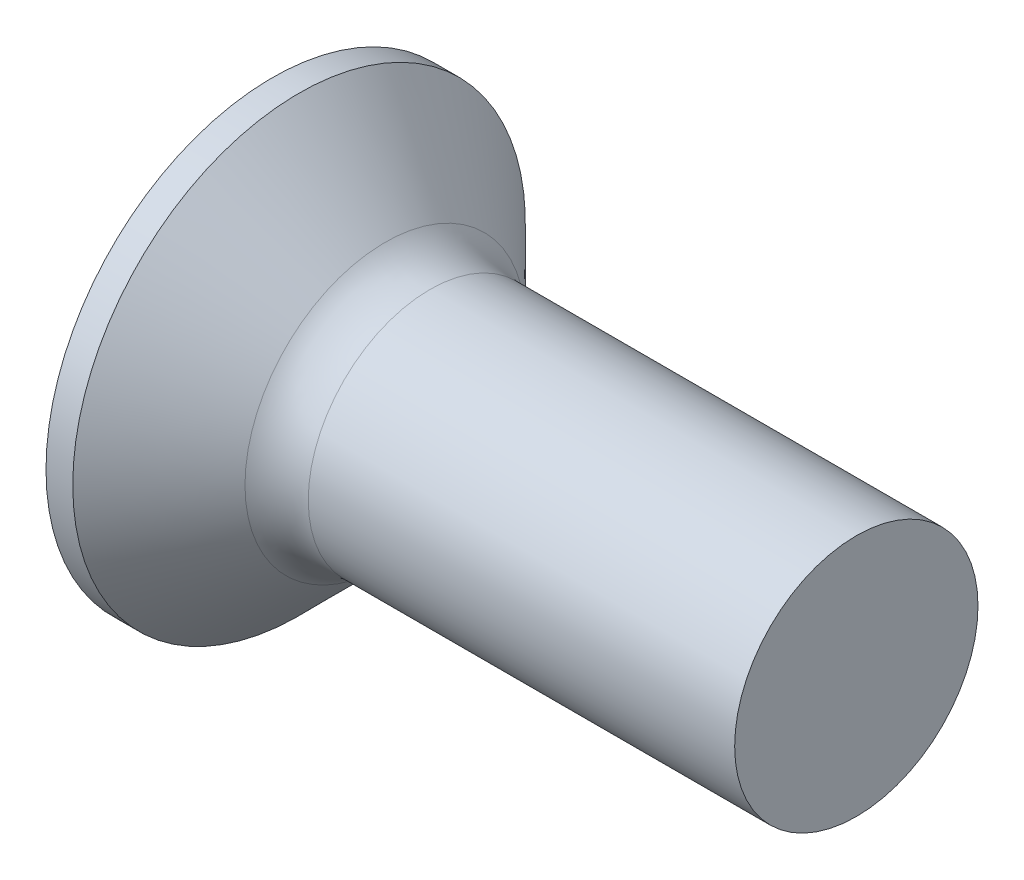
SolidWorks part; units mm, degrees
ref_plane "Plane1" through (0, 0, 0) normal (0, 0, 1) x (1, 0, 0)
ref_plane "Plane2" through (0, 0, 0) normal (0, 1, 0) x (1, 0, 0)
ref_plane "Plane3" through (0, 0, 0) normal (1, 0, 0) x (0, 0, -1)
sketch "BodySke" plane through (0, 0, 0) normal (0, 0, 1) x (1, 0, 0)
  line L0 (0, 0) -> (0, 4.65)
  line L1 (0, 4.65) -> (0.55, 4.65)
  line L2 (2.7, 2.5) -> (12, 2.5)
  line L3 (12, 2.5) -> (12, 0)
  line L4 (12, 0) -> (0, 0)
  line L5 (-6.35, 0) -> (82.55, 0) construction
  line L6 (2.7, -2.5) -> (12, -2.5) construction
  line L7 (0.55, -4.65) -> (2.7, -2.5) construction
  line L8 (0.55, 4.65) -> (2.7, 2.5)
  line L9 (0, -4.65) -> (0.55, -4.65) construction
  line L10 (3.5, 4.0875) -> (3.5, -5.4375) construction
  line L11 (0, 6.35) -> (0, -3.175) construction
  dimension "Diameter" = 5
  dimension "Length" = 12
  dimension "Head_ht" = 2.7
  dimension "Head_dia" = 9.3
  dimension "Head_ang" = 90
  dimension "D6" = 0.55
  dimension "Advance" = 0.8
  dimension "Thread_nom" = 12
revolve "Base-Revolve" add sketch "BodySke"
cosmetic thread "ThreadCosmetic" [suppressed]
fillet "Fillet1" radius 1.3 1 edges at (2.7, 0, 2.5)
sketch "Sketch3" plane through (0, 0, 0) normal (-1, 0, 0) x (0, 0, 1)
  line L0 (-0.515, 2.45) -> (0.515, 2.45)
  line L1 (0.515, 2.45) -> (0.515, -2.45)
  line L2 (0.515, -2.45) -> (-0.515, -2.45)
  line L3 (-0.515, -2.45) -> (-0.515, 2.45)
  dimension "D1" = 2.45
  dimension "Cross_dia" = 4.9
  dimension "D2" = 0.515
  dimension "Cross_width" = 1.03
ref_plane "Plane4" through (3.05, 0, 0) normal (-1, 0, 0) x (0, 0, 1)
sketch "Sketch4" plane through (3.05, 0, 0) normal (-1, 0, 0) x (0, 0, 1)
  line L0 (-0.515, 0.9293) -> (0.515, 0.9293)
  line L3 (0.515, 0.9293) -> (0.515, -0.9293)
  line L4 (0.515, -0.9293) -> (-0.515, -0.9293)
  line L5 (-0.515, -0.9293) -> (-0.515, 0.9293)
  dimension "D1" = 1.03
  dimension "D2" = 1.8587
  dimension "D3" = 0.515
  dimension "D4" = 0.9293
loft "Recess" cut profiles "Sketch3", "Sketch4"
pattern_circular "RecPat" count 2 every 90 about axis through (0, 0, 0) along (1, 0, 0) of "Recess"
sketch "RecCorSke" plane through (0, 0, 0) normal (0, 0, 1) x (1, 0, 0)
  line L0 (-3.175, 0) -> (15.875, 0) construction
  line L2 (0, 0) -> (0, 1.0643)
  line L3 (0, 1.0643) -> (3.05, 0.851)
  line L4 (3.05, 0.851) -> (3.3265, 0)
  line L5 (3.3265, 0) -> (0, 0)
  dimension "Diameter" = 1.702
  dimension "Depth" = 3.05
  dimension "Draft_angle" = 4
  dimension "Bottom_angle" = 18
revolve "RecessCore" cut sketch "RecCorSke" angle 360 about L0
sketch "ThdSchSke" plane through (0, 0, 0) normal (0, 0, 1) x (1, 0, 0)
  line L0 (3.5, -2.055) -> (3.1884, -2.5)
  line L1 (3.5, -2.055) -> (3.8116, -2.5)
  line L2 (3.8116, -2.5) -> (3.8116, -3.125)
  line L3 (-3.175, 0) -> (5.1513, 0) construction
  line L5 (3.8116, -3.125) -> (3.1884, -3.125)
  line L6 (3.1884, -3.125) -> (3.1884, -2.5)
  line L7 (0, 4.65) -> (0, -4.65) construction
  dimension "Thread_minor" = 4.11
  dimension "Diameter" = 5
  dimension "Start" = 3.5
  dimension "SideAngle" = 55
  dimension "VeeAngle" = 70
  dimension "Overcut" = 6.25
revolve "ThreadSchematic" [suppressed] cut sketch "ThdSchSke" angle 360 about L3
pattern_linear "ThdSchPat" [suppressed]
equation "\"D1@Sketch3\" = \"Cross_dia@Sketch3\" / 2"
equation "\"D2@Sketch3\" = \"Cross_width@Sketch3\" / 2"
equation "\"Depth@RecCorSke\" = \"Cross_depth@Plane4\""
equation "\"D1@Sketch4\" = \"Cross_width@Sketch3\""
equation "\"D2@Sketch4\" = \"Cross_dia@Sketch3\" - 2.0 * \"Cross_depth@Plane4\" * tan(26.5  * 0.017453292)"
equation "\"D3@Sketch4\" = \"D1@Sketch4\" / 2"
equation "\"D4@Sketch4\" = \"D2@Sketch4\" / 2"
equation "\"Thread_length@ThreadCosmetic\" = ((sgn( (\"Length@BodySke\" - \"Advance@BodySke\" * 1.0 - \"Head_ht@BodySke\" ) - \"Thread_nom@BodySke\" )-1)*( (\"Length@BodySke\" - \"Advance@BodySke\" * 1.0 - \"Head_ht@BodySke\" ) - \"Thread_nom@BodySke\" ))/-2+ \"Thread_nom@BodySke\""
equation "\"Thread_minor@ThdSchSke\" = \"Thread_minor@ThreadCosmetic\""
equation "\"Diameter@ThdSchSke\" = \"Diameter@BodySke\""
equation "\"Overcut@ThdSchSke\" = \"Diameter@BodySke\" * 1.25"
equation "\"Start@ThdSchSke\" = 0.000001 + \"Length@BodySke\" - \"Thread_length@ThreadCosmetic\"  '---Countersunk---"
equation "\"Num_threads@ThdSchPat\" = int( \"Thread_length@ThreadCosmetic\" / \"Advance@BodySke\" + 0.999 )  + 1"
equation "\"Advance@ThdSchPat\" = \"Thread_length@ThreadCosmetic\" /  (\"Num_threads@ThdSchPat\" - 1) 'relax it"
